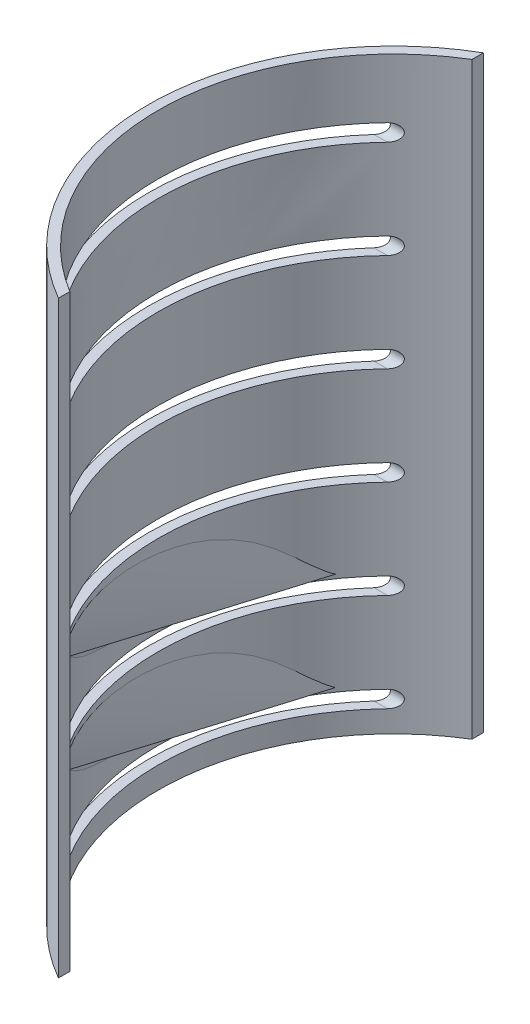
SolidWorks part; units mm, degrees
material "POLYURETHANE (11671)"
ref_plane "Front Plane" through (0, 0, 0) normal (0, 0, 1) x (1, 0, 0)
ref_plane "Top Plane" through (0, 0, 0) normal (0, 1, 0) x (1, 0, 0)
ref_plane "Right Plane" through (0, 0, 0) normal (1, 0, 0) x (0, 0, -1)
sketch "Sketch2" plane through (0, 0, 0) normal (0, 1, 0) x (1, 0, 0)
  line L0 (-12.5, 21.6506) -> (-12.5, 20.4878)
  line L1 (-12.5, -20.4878) -> (-12.5, -21.6506)
  arc A0 (-12.5, 21.6506) -> (-12.5, -21.6506) centre (0, 0) ccw
  arc A1 (-12.5, 20.4878) -> (-12.5, -20.4878) centre (0, 0) ccw
  dimension "D1" = 50
  dimension "D3" = 48
  dimension "D4" = 1
  dimension "D2" = 12.5
extrude "Boss-Extrude1" add sketch "Sketch2" along normal blind 60
sketch "Sketch3" plane through (0, 0, 0) normal (1, 0, 0) x (0, 0, -1)
  line L0 (21.6506, 60) -> (21.6506, 0) construction
  line L1 (-21.6506, 60) -> (-21.6506, 0) construction
  line L2 (21.6506, 60) -> (21.6506, 0)
  line L3 (-21.6506, 60) -> (-21.6506, 0)
  line L4 (-16.6506, 3.0807) -> (16.6506, 3.0807) construction
  line L5 (-16.6506, 3.9413) -> (16.6506, 3.9413)
  line L6 (-16.6506, 2.22) -> (16.6506, 2.22)
  line L8 (-20.4878, 0) -> (20.4878, 0) construction
  line L9 (-16.6506, 13.0807) -> (16.6506, 13.0807) construction
  line L10 (-16.6506, 13.9413) -> (16.6506, 13.9413)
  line L11 (-16.6506, 12.22) -> (16.6506, 12.22)
  line L12 (-16.6506, 23.0807) -> (16.6506, 23.0807) construction
  line L13 (-16.6506, 23.9413) -> (16.6506, 23.9413)
  line L14 (-16.6506, 22.22) -> (16.6506, 22.22)
  line L15 (-16.6506, 33.0807) -> (16.6506, 33.0807) construction
  line L16 (-16.6506, 33.9413) -> (16.6506, 33.9413)
  line L17 (-16.6506, 32.22) -> (16.6506, 32.22)
  line L18 (-16.6506, 43.0807) -> (16.6506, 43.0807) construction
  line L19 (-16.6506, 43.9413) -> (16.6506, 43.9413)
  line L20 (-16.6506, 42.22) -> (16.6506, 42.22)
  line L21 (-16.6506, 53.0807) -> (16.6506, 53.0807) construction
  line L22 (-16.6506, 53.9413) -> (16.6506, 53.9413)
  line L23 (-16.6506, 52.22) -> (16.6506, 52.22)
  arc A0 (-16.6506, 3.9413) -> (-16.6506, 2.22) centre (-16.6506, 3.0807) ccw
  arc A1 (16.6506, 2.22) -> (16.6506, 3.9413) centre (16.6506, 3.0807) ccw
  arc A2 (-16.6506, 13.9413) -> (-16.6506, 12.22) centre (-16.6506, 13.0807) ccw
  arc A3 (16.6506, 12.22) -> (16.6506, 13.9413) centre (16.6506, 13.0807) ccw
  arc A4 (-16.6506, 23.9413) -> (-16.6506, 22.22) centre (-16.6506, 23.0807) ccw
  arc A5 (16.6506, 22.22) -> (16.6506, 23.9413) centre (16.6506, 23.0807) ccw
  arc A6 (-16.6506, 33.9413) -> (-16.6506, 32.22) centre (-16.6506, 33.0807) ccw
  arc A7 (16.6506, 32.22) -> (16.6506, 33.9413) centre (16.6506, 33.0807) ccw
  arc A8 (-16.6506, 43.9413) -> (-16.6506, 42.22) centre (-16.6506, 43.0807) ccw
  arc A9 (16.6506, 42.22) -> (16.6506, 43.9413) centre (16.6506, 43.0807) ccw
  arc A10 (-16.6506, 53.9413) -> (-16.6506, 52.22) centre (-16.6506, 53.0807) ccw
  arc A11 (16.6506, 52.22) -> (16.6506, 53.9413) centre (16.6506, 53.0807) ccw
  point P6 (0, 3.0807)
  point P16 (0, 13.0807)
  point P23 (0, 23.0807)
  point P30 (0, 33.0807)
  point P37 (0, 43.0807)
  point P44 (0, 53.0807)
  dimension "D1" = 5
  dimension "D2" = 5
  dimension "D3" = 2.22
  dimension "D4" = 6
extrude "Cut-Extrude1" cut sketch "Sketch3" against normal through all both and the other way through all contours L23 A11 L22 A10 | L20 A9 L19 A8 | L17 A7 L16 A6 | L14 A5 L13 A4 | L11 A3 L10 A2 | L6 A1 L5 A0
